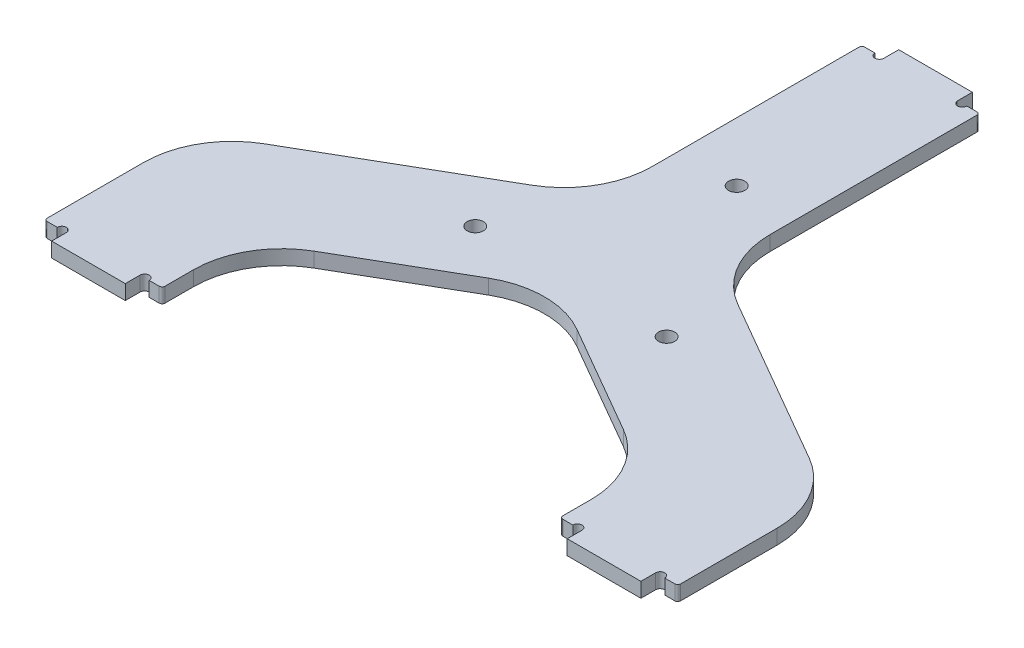
SolidWorks part; units mm, degrees
material "Hexcel AS4C (3000 丝)"
ref_plane "前视基准面" through (0, 0, 0) normal (0, 0, 1) x (1, 0, 0)
ref_plane "上视基准面" through (0, 0, 0) normal (0, 1, 0) x (1, 0, 0)
ref_plane "右视基准面" through (0, 0, 0) normal (1, 0, 0) x (0, 0, -1)
other "Configuration Table"
sketch "草图1" plane through (0, 0, 0) normal (0, 1, 0) x (1, 0, 0)
  line L0 (0, 66.645) -> (0, 0) construction
  line L1 (0, 0) -> (-61.257, -35.3667) construction
  line L2 (0, 0) -> (64.9836, -37.5183) construction
  line L3 (-20, 100) -> (20, 100)
  line L4 (20, 100) -> (20, 11.547)
  line L5 (20, 11.547) -> (87.5, -27.4241)
  line L7 (0, 0) -> (89.4221, 51.6279) construction
  line L8 (0, 0) -> (0, -63.446) construction
  line L9 (0, 0) -> (-78.7072, 45.4416) construction
  line L10 (0, -23.094) -> (67.5, -62.0652)
  line L11 (-20, 100) -> (-20, 11.547)
  line L12 (-20, 11.547) -> (-87.5, -27.4241)
  line L14 (0, -23.094) -> (-67.5, -62.0652)
  line L15 (-116.2493, -90) -> (125.7289, -90) construction
  line L16 (87.5, -27.4241) -> (107.5, -38.9711)
  line L17 (107.5, -38.9711) -> (107.5, -90)
  line L18 (67.5, -62.0652) -> (67.5, -90)
  line L19 (67.5, -90) -> (107.5, -90)
  line L20 (-67.5, -90) -> (-107.5, -90)
  line L21 (-67.5, -62.0652) -> (-67.5, -90)
  line L22 (-107.5, -38.9711) -> (-107.5, -90)
  line L23 (-87.5, -27.4241) -> (-107.5, -38.9711)
  point P15 (77.9423, -45)
  point P17 (0, 100)
  dimension "D1" = 190
  dimension "D2" = 120
  dimension "D3" = 60
  dimension "D4" = 60
  dimension "D5" = 100
  dimension "D6" = 135
  dimension "D7" = 20
  dimension "D8" = 40
extrude "凸台-拉伸1" add sketch "草图1" along normal blind 5
sketch "草图3" plane through (0, 5, 0) normal (0, 1, 0) x (1, 0, 0)
  line L0 (0, 0) -> (0, 55.4456) construction
  line L1 (0, 0) -> (-62.5545, -36.1159) construction
  line L2 (0, 0) -> (50.5729, -29.1983) construction
  line L3 (107.5, -38.9711) -> (20, 11.547) construction
  line L4 (0, -23.094) -> (67.5, -62.0652) construction
  line L5 (-20, 11.547) -> (-107.5, -38.9711) construction
  line L6 (-67.5, -62.0652) -> (0, -23.094) construction
  line L7 (-32.475, -18.7494) -> (32.475, -18.7494) construction
  circle A0 centre (0, 37.4989) radius 2.75
  circle A1 centre (32.475, -18.7494) radius 2.75
  circle A2 centre (-32.475, -18.7494) radius 2.75
  circle A3 centre (0, 0) radius 37.4989 construction
  dimension "D1" = 5.5
  dimension "D2" = 64.95
extrude "切除-拉伸1" cut sketch "草图3" against normal blind 5 contours A0 | A1 | A2
sketch "草图4" plane through (0, 5, 0) normal (0, 1, 0) x (1, 0, 0)
  line L0 (0, 0) -> (0, 135.8563) construction
  line L1 (20, 100) -> (-20, 100) construction
  line L2 (-12.5, 100) -> (12.5, 100)
  line L3 (-12.5, 100) -> (-12.5, 105)
  line L4 (-12.5, 105) -> (12.5, 105)
  line L5 (12.5, 100) -> (12.5, 105)
  line L6 (87.5, -13.6383) -> (87.5, -101.0311) construction
  line L7 (67.5, -62.0652) -> (67.5, -90) construction
  line L8 (107.5, -90) -> (107.5, -38.9711) construction
  line L9 (67.5, -90) -> (107.5, -90) construction
  line L10 (75, -90) -> (100, -90)
  line L11 (75, -90) -> (75, -95)
  line L12 (75, -95) -> (100, -95)
  line L13 (100, -90) -> (100, -95)
  line L14 (-75, -95) -> (-100, -95)
  line L15 (-100, -90) -> (-100, -95)
  line L16 (-75, -90) -> (-100, -90)
  line L17 (-75, -90) -> (-75, -95)
  line M22 (-107.5, -90) -> (-67.5, -90)
  line M25 (67.5, -90) -> (107.5, -90)
  dimension "D3" = 5
  dimension "D1" = 5
  dimension "D2" = 25
  dimension "D4" = 25
extrude "凸台-拉伸2" add sketch "草图4" against normal blind 5 contours L17 L15 L14 M22 | L13 L11 L12 M25 | L4 L5 L2 L3
sketch "草图5" plane through (0, 5, 0) normal (0, 1, 0) x (1, 0, 0)
  line L0 (20, 100) -> (12.5, 100) construction
  line L1 (-12.5, 100) -> (-12.5, 105) construction
  line L2 (12.5, 100) -> (12.5, 105) construction
  line L3 (-12.5, 100) -> (-20, 100) construction
  line L4 (-75, -90) -> (-67.5, -90) construction
  line L5 (-107.5, -90) -> (-100, -90) construction
  line L6 (100, -90) -> (107.5, -90) construction
  line L7 (67.5, -90) -> (75, -90) construction
  line L8 (-75, -90) -> (-75, -95) construction
  line L9 (-100, -90) -> (-100, -95) construction
  line L10 (75, -90) -> (75, -95) construction
  line L11 (100, -90) -> (100, -95) construction
  circle A0 centre (14.05, 100) radius 1.55
  circle A1 centre (-14.05, 100) radius 1.55
  circle A2 centre (-73.45, -90) radius 1.55
  circle A3 centre (-101.55, -90) radius 1.55
  circle A4 centre (101.55, -90) radius 1.55
  circle A5 centre (73.45, -90) radius 1.55
  dimension "D2" = 3.1
extrude "切除-拉伸2" cut sketch "草图5" against normal blind 5
fillet "圆角1" radius 30 7 edges at (-107.5, 2.5, 38.9711) (-67.5, 2.5, 62.0652) (67.5, 2.5, 62.0652) (107.5, 2.5, 38.9711) (20, 2.5, -11.547) (0, 2.5, 23.094) (-20, 2.5, -11.547)
fillet "圆角2" radius 1 6 edges at (-67.5, 2.5, 90) (-107.5, 2.5, 90) (67.5, 2.5, 90) (107.5, 2.5, 90) (-20, 2.5, -100) (20, 2.5, -100)
